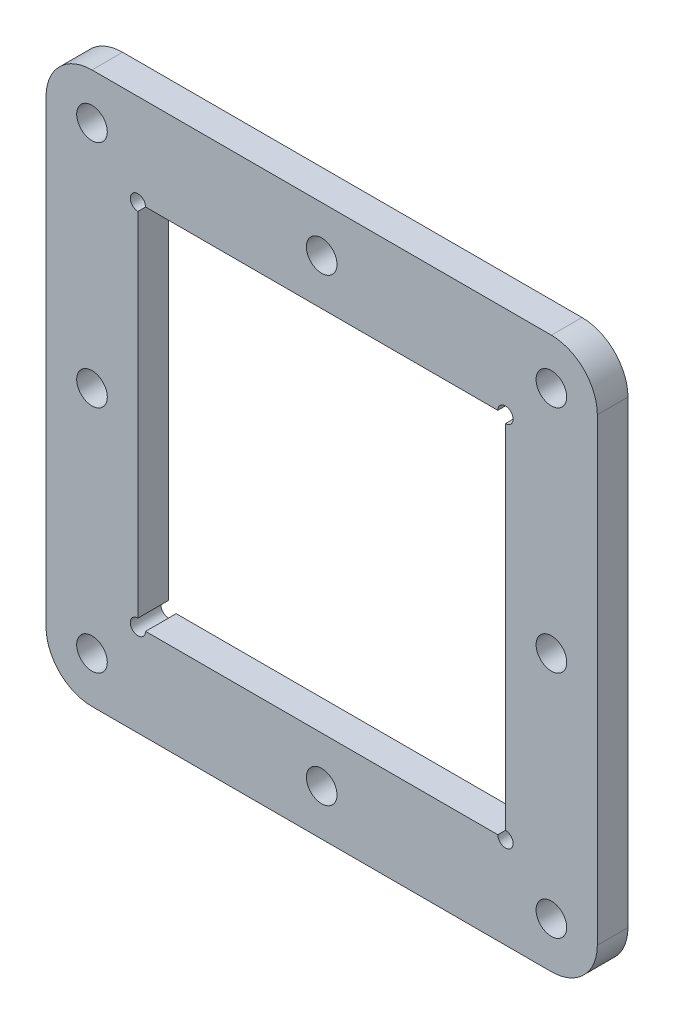
SolidWorks part; units mm, degrees
ref_plane "Front Plane" through (0, 0, 0) normal (0, 0, 1) x (1, 0, 0)
ref_plane "Top Plane" through (0, 0, 0) normal (0, 1, 0) x (1, 0, 0)
ref_plane "Right Plane" through (0, 0, 0) normal (1, 0, 0) x (0, 0, -1)
sketch "Sketch2" plane through (0, 0, 0) normal (0, 0, 1) x (1, 0, 0)
  line L0 (-75, 75) -> (75, 75) construction
  line L1 (-75, 90) -> (75, 90)
  line L2 (-90, 75) -> (-90, -75)
  line L3 (-75, -90) -> (75, -90)
  line L4 (90, 75) -> (90, -75)
  line L5 (-90, 90) -> (90, -90) construction
  line L6 (-90, -90) -> (90, 90) construction
  line L7 (75, 75) -> (75, -75) construction
  line L8 (75, -75) -> (-75, -75) construction
  line L9 (-75, -75) -> (-75, 75) construction
  line L11 (-60, 60) -> (60, 60)
  line L12 (-60, 60) -> (-60, -60)
  line L13 (-60, -60) -> (60, -60)
  line L14 (60, 60) -> (60, -60)
  line L15 (-60, 60) -> (60, -60) construction
  line L16 (-60, -60) -> (60, 60) construction
  arc A0 (-90, -75) -> (-75, -90) centre (-75, -75) ccw
  arc A1 (75, -90) -> (90, -75) centre (75, -75) ccw
  arc A2 (75, 90) -> (90, 75) centre (75, 75) cw
  arc A3 (-75, 90) -> (-90, 75) centre (-75, 75) ccw
  circle A4 centre (-75, 75) radius 5
  circle A5 centre (0, 75) radius 5
  circle A6 centre (75, 75) radius 5
  circle A7 centre (-75, 0) radius 5
  circle A8 centre (0, 0) radius 5 construction
  circle A9 centre (75, 0) radius 5
  circle A10 centre (-75, -75) radius 5
  circle A11 centre (0, -75) radius 5
  circle A12 centre (75, -75) radius 5
  point P0 (0, 0)
  dimension "D3" = 15
  dimension "D4" = 10
  dimension "D1" = 180
  dimension "D2" = 180
  dimension "D8" = 120
  dimension "D7" = 3
extrude "Boss-Extrude1" add sketch "Sketch2" along normal blind 10
sketch "Sketch3" plane through (0, 0, 10) normal (0, 0, 1) x (1, 0, 0)
  circle A0 centre (-60, 60) radius 2.5
  circle A1 centre (60, 60) radius 2.5
  circle A2 centre (60, -60) radius 2.5
  circle A3 centre (-60, -60) radius 2.5
  dimension "D1" = 5
extrude "Cut-Extrude1" cut sketch "Sketch3" against normal blind 10
